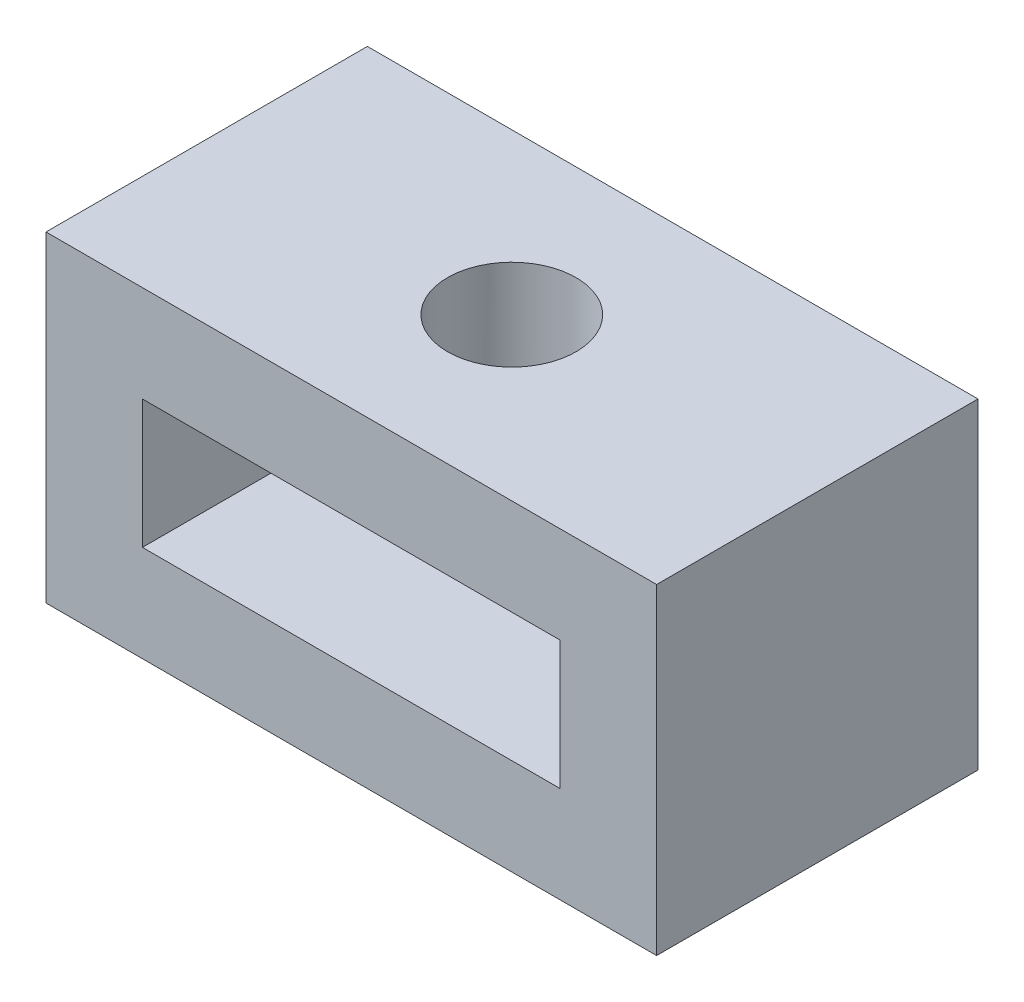
SolidWorks part; units mm, degrees
ref_plane "Front Plane" through (0, 0, 0) normal (0, 0, 1) x (1, 0, 0)
ref_plane "Top Plane" through (0, 0, 0) normal (0, 1, 0) x (1, 0, 0)
ref_plane "Right Plane" through (0, 0, 0) normal (1, 0, 0) x (0, 0, -1)
sketch "Sketch3" plane through (0, 0, 0) normal (0, 0, 1) x (1, 0, 0)
  line L1 (27.6967, 40.5855) -> (40.6967, 40.5855)
  line L2 (27.6967, 40.5855) -> (27.6967, 36.5855)
  line L3 (27.6967, 36.5855) -> (40.6967, 36.5855)
  line L4 (40.6967, 40.5855) -> (40.6967, 36.5855)
  line L5 (27.6967, 40.5855) -> (40.6967, 36.5855) construction
  line L6 (27.6967, 36.5855) -> (40.6967, 40.5855) construction
  line L7 (24.6967, 33.5855) -> (43.6967, 33.5855)
  line L8 (24.6967, 33.5855) -> (24.6967, 43.5855)
  line L9 (24.6967, 43.5855) -> (43.6967, 43.5855)
  line L10 (43.6967, 33.5855) -> (43.6967, 43.5855)
  line L11 (24.6967, 33.5855) -> (43.6967, 43.5855) construction
  line L12 (24.6967, 43.5855) -> (43.6967, 33.5855) construction
  point P0 (34.1967, 38.5855)
  point P5 (34.1967, 38.5855)
  dimension "D1" = 13
  dimension "D2" = 4
  dimension "D3" = 19
  dimension "D4" = 10
extrude "Boss-Extrude1" add sketch "Sketch3" along normal blind 10
sketch "Sketch4" plane through (0, 43.5855, 0) normal (0, 1, 0) x (1, 0, 0)
  circle A0 centre (34.1727, -4.982) radius 2
extrude "Cut-Extrude1" cut sketch "Sketch4" against normal blind 4
